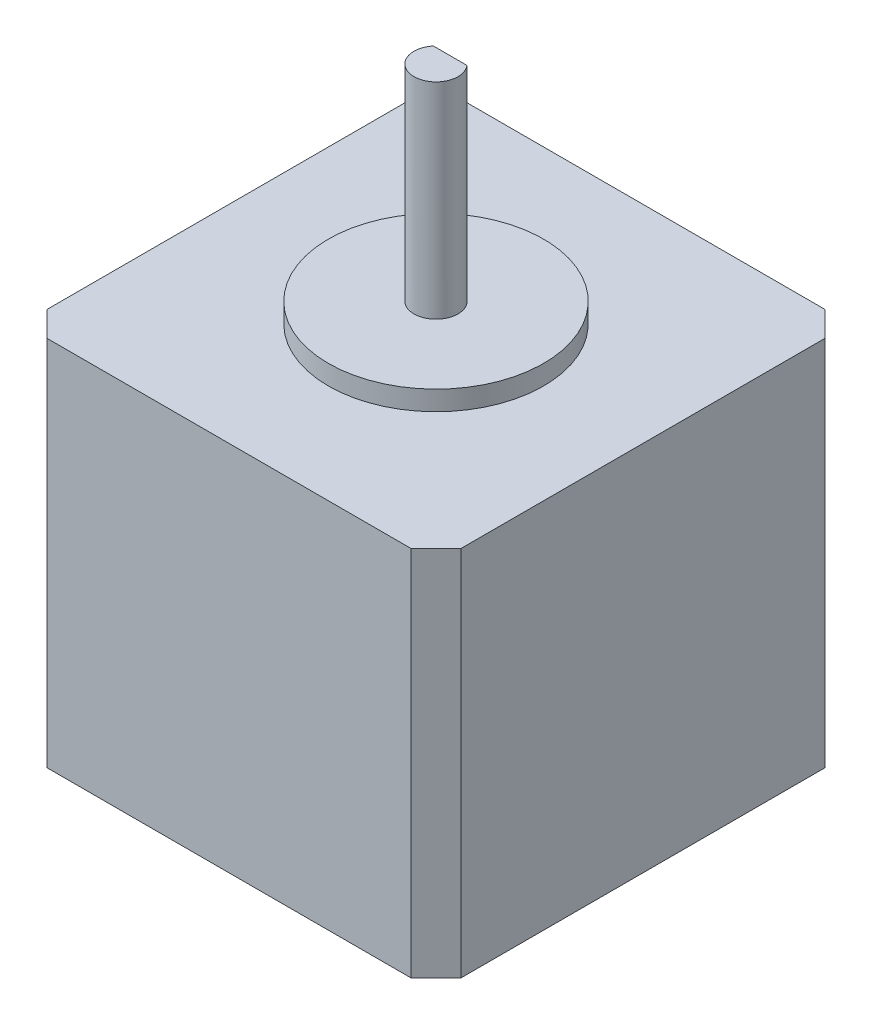
SolidWorks part; units mm, degrees
ref_plane "Front Plane" through (0, 0, 0) normal (0, 0, 1) x (1, 0, 0)
ref_plane "Top Plane" through (0, 0, 0) normal (0, 1, 0) x (1, 0, 0)
ref_plane "Right Plane" through (0, 0, 0) normal (1, 0, 0) x (0, 0, -1)
sketch "Sketch1" plane through (0, 0, 0) normal (0, 1, 0) x (1, 0, 0)
  line L1 (-21.15, -21.15) -> (21.15, -21.15)
  line L2 (-21.15, -21.15) -> (-21.15, 21.15)
  line L3 (-21.15, 21.15) -> (21.15, 21.15)
  line L4 (21.15, -21.15) -> (21.15, 21.15)
  line L5 (-21.15, -21.15) -> (21.15, 21.15) construction
  line L6 (-21.15, 21.15) -> (21.15, -21.15) construction
  point P0 (0, 0)
  dimension "D1" = 42.3
  dimension "D2" = 42.3
extrude "Boss-Extrude1" add sketch "Sketch1" along normal blind 38
chamfer "Chamfer1" distance 2.54 angle 45 4 edges at (-21.15, 19, -21.15) (21.15, 19, -21.15) (21.15, 19, 21.15) (-21.15, 19, 21.15)
sketch "Sketch2" plane through (0, 38, 0) normal (0, 1, 0) x (1, 0, 0)
  circle A0 centre (0, 0) radius 11
extrude "Boss-Extrude2" add sketch "Sketch2" along normal blind 2
sketch "Sketch3" plane through (0, 40, 0) normal (0, 1, 0) x (1, 0, 0)
  circle A0 centre (0, 0) radius 2.25
extrude "Boss-Extrude3" add sketch "Sketch3" along normal blind 21
sketch "Sketch4" plane through (0, 61, 0) normal (0, 1, 0) x (1, 0, 0)
  line L1 (-1.7184, 3.0475) -> (1.7184, 3.0475)
  line L2 (-1.7184, 3.0475) -> (-1.7184, 1.4525)
  line L3 (-1.7184, 1.4525) -> (1.7184, 1.4525)
  line L4 (1.7184, 3.0475) -> (1.7184, 1.4525)
  line L5 (-1.7184, 3.0475) -> (1.7184, 1.4525) construction
  line L6 (-1.7184, 1.4525) -> (1.7184, 3.0475) construction
  circle A0 centre (0, 0) radius 2.25 construction
  point P0 (0, 2.25)
extrude "Cut-Extrude1" cut sketch "Sketch4" against normal blind 18
